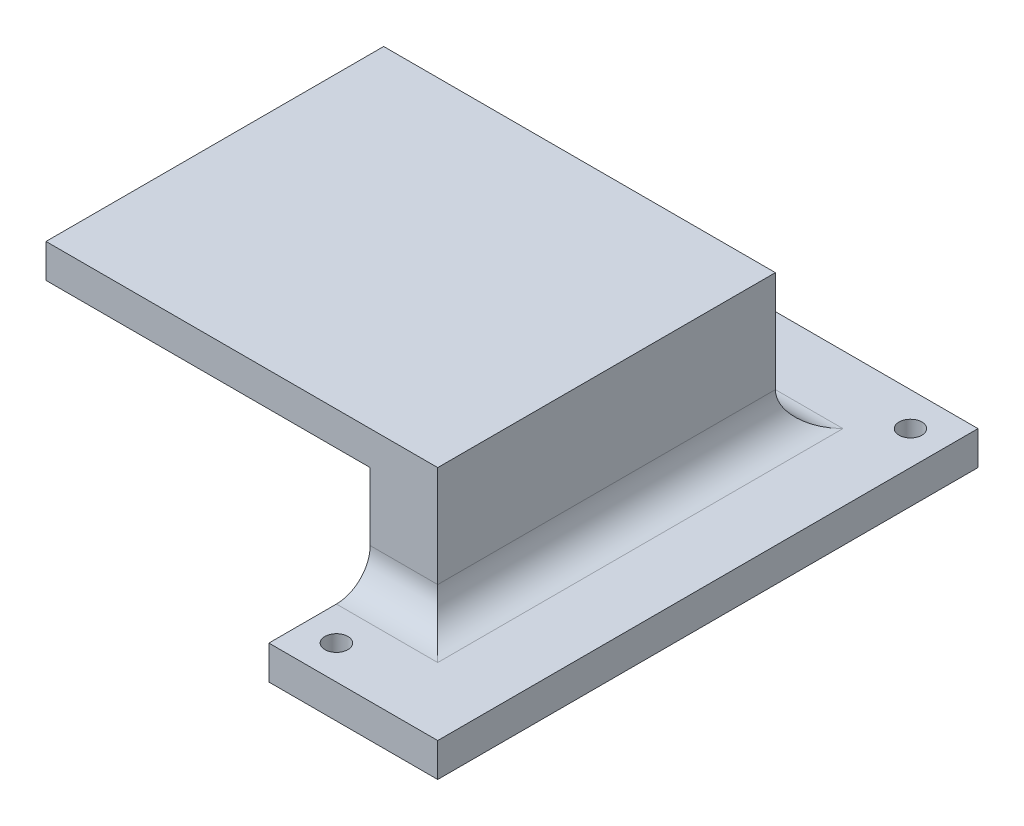
SolidWorks part; units mm, degrees
ref_plane "前视基准面" through (0, 0, 0) normal (0, 0, 1) x (1, 0, 0)
ref_plane "上视基准面" through (0, 0, 0) normal (0, 1, 0) x (1, 0, 0)
ref_plane "右视基准面" through (0, 0, 0) normal (1, 0, 0) x (0, 0, -1)
sketch "草图1" plane through (0, 0, 0) normal (0, 1, 0) x (1, 0, 0)
  line L1 (-24, -27.5) -> (24, -27.5)
  line L2 (-24, -27.5) -> (-24, 27.5)
  line L3 (-24, 27.5) -> (24, 27.5)
  line L4 (24, -27.5) -> (24, 27.5)
  line L5 (-24, -27.5) -> (24, 27.5) construction
  line L6 (-24, 27.5) -> (24, -27.5) construction
  line L31 (-24, 27.5) -> (49, 27.5)
  line L32 (-24, 27.5) -> (-24, 52.5)
  line L33 (-24, 52.5) -> (49, 52.5)
  line L34 (49, 27.5) -> (49, 52.5)
  line L35 (24, -27.5) -> (49, -27.5)
  line L36 (24, -27.5) -> (24, 52.5)
  line L37 (24, 52.5) -> (49, 52.5)
  line L38 (49, -27.5) -> (49, 52.5)
  circle A6 centre (-19, 47.5) radius 1.7
  circle A7 centre (44, 47.5) radius 1.7
  circle A8 centre (29, -22.5) radius 1.7
  point P0 (0, 0)
  dimension "D11" = 3.4
  dimension "D12" = 5
  dimension "D14" = 3.4
  dimension "D8" = 3.4
  dimension "D1" = 48
  dimension "D2" = 55
  dimension "D3" = 25
  dimension "D4" = 25
  dimension "D6" = 5
  dimension "D7" = 5
  dimension "D9" = 5
  dimension "D10" = 5
  dimension "D13" = 5
extrude "凸台-拉伸1" add sketch "草图1" along normal blind 5
sketch "草图2" plane through (0, 5, 0) normal (0, 1, 0) x (1, 0, 0)
  line L1 (-24, 27.5) -> (34, 27.5)
  line L2 (-24, 27.5) -> (-24, 37.5)
  line L3 (-24, 37.5) -> (34, 37.5)
  line L4 (34, 27.5) -> (34, 37.5)
  line L5 (34, 37.5) -> (24, 37.5)
  line L6 (34, 37.5) -> (34, -12.5)
  line L7 (34, -12.5) -> (24, -12.5)
  line L8 (24, 37.5) -> (24, -12.5)
  line L10 (24, -27.5) -> (24, 27.5) construction
  dimension "D1" = 10
  dimension "D2" = 10
  dimension "D3" = 50
extrude "凸台-拉伸2" add sketch "草图2" along normal blind 15
sketch "草图3" plane through (0, 20, 0) normal (0, 1, 0) x (1, 0, 0)
  line L1 (-24, 37.5) -> (34, 37.5)
  line L2 (-24, 37.5) -> (-24, -12.5)
  line L3 (-24, -12.5) -> (34, -12.5)
  line L4 (34, 37.5) -> (34, -12.5)
extrude "凸台-拉伸3" add sketch "草图3" along normal blind 5
sketch "草图4" plane through (24, 0, 0) normal (-1, 0, 0) x (0, 0, 1)
  line L0 (27.5, 0) -> (-27.5, 0) construction
  line L1 (-6.5, 0) -> (-1.5, 0)
  line L2 (-6.5, 0) -> (-6.5, 20)
  line L3 (-6.5, 20) -> (-1.5, 20)
  line L4 (-1.5, 0) -> (-1.5, 20)
  line L5 (-27.5, 20) -> (12.5, 20) construction
  line L7 (-27.5, 20) -> (-27.5, 0) construction
  dimension "D1" = 26
  dimension "D2" = 5
extrude "凸台-拉伸4" add sketch "草图4" along normal blind 7
sketch "草图6" plane through (0, 0, -1.5) normal (0, 0, 1) x (1, 0, 0)
  line L0 (24, 0) -> (24, 20) construction
  line L1 (17, 20) -> (24, 20) construction
  circle A0 centre (20.65, 15) radius 1.35
  circle A1 centre (20.65, 5) radius 1.35
  dimension "D3" = 2.7
  dimension "D4" = 2.7
  dimension "D1" = 3.35
  dimension "D2" = 5
  dimension "D5" = 10
  dimension "D6" = 3.35
extrude "切除-拉伸1" cut sketch "草图6" against normal blind 8
fillet "圆角1" radius 5 3 edges at (5, 5, -37.5) (29, 5, 12.5) (34, 5, -12.5)
